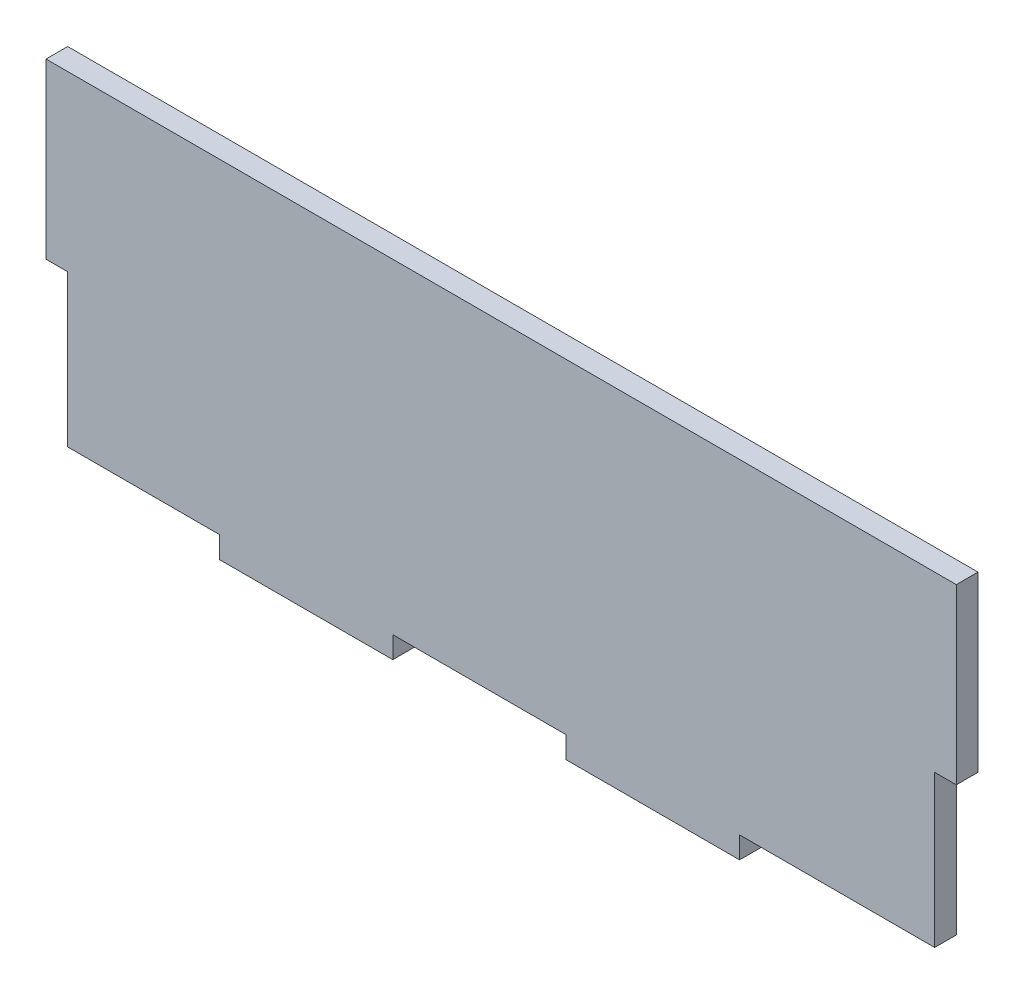
SolidWorks part; units mm, degrees
ref_plane "Front Plane" through (0, 0, 0) normal (0, 0, 1) x (1, 0, 0)
ref_plane "Top Plane" through (0, 0, 0) normal (0, 1, 0) x (1, 0, 0)
ref_plane "Right Plane" through (0, 0, 0) normal (1, 0, 0) x (0, 0, -1)
sketch "Sketch1" plane through (0, 0, 0) normal (0, 0, 1) x (1, 0, 0)
  line L0 (0, 101.6) -> (0, 50.8)
  line L1 (50.8, 0) -> (260.35, 0) construction
  line L2 (0, 0) -> (0, 101.6) construction
  line L3 (0, 101.6) -> (266.7, 101.6)
  line L4 (266.7, 50.8) -> (266.7, 101.6)
  line L5 (6.35, 0) -> (0, 0) construction
  line L6 (6.35, 6.35) -> (50.8, 6.35)
  line L7 (0, 50.8) -> (6.35, 50.8)
  line L8 (6.35, 50.8) -> (6.35, 6.35)
  line L9 (266.7, 50.8) -> (260.35, 50.8)
  line L10 (260.35, 50.8) -> (260.35, 6.35)
  line L11 (50.8, 6.35) -> (50.8, 0)
  line L12 (6.35, 0) -> (6.35, 6.35) construction
  line L13 (6.35, 0) -> (50.8, 0) construction
  line L14 (50.8, 0) -> (101.6, 0)
  line L15 (101.6, 0) -> (101.6, 6.35)
  line L16 (101.6, 6.35) -> (152.4, 6.35)
  line L17 (152.4, 6.35) -> (152.4, 0)
  line L18 (152.4, 0) -> (203.2, 0)
  line L19 (203.2, 0) -> (203.2, 6.35)
  line L20 (203.2, 6.35) -> (254, 6.35)
  line L21 (260.35, 0) -> (260.35, 6.35) construction
  line L22 (254, 6.35) -> (260.35, 6.35)
  dimension "D1" = 6.35
  dimension "D2" = 266.7
  dimension "D3" = 50.8
  dimension "D4" = 6.35
  dimension "D5" = 44.45
  dimension "D6" = 6.35
  dimension "D7" = 50.8
extrude "Boss-Extrude1" add sketch "Sketch1" along normal blind 6.35
